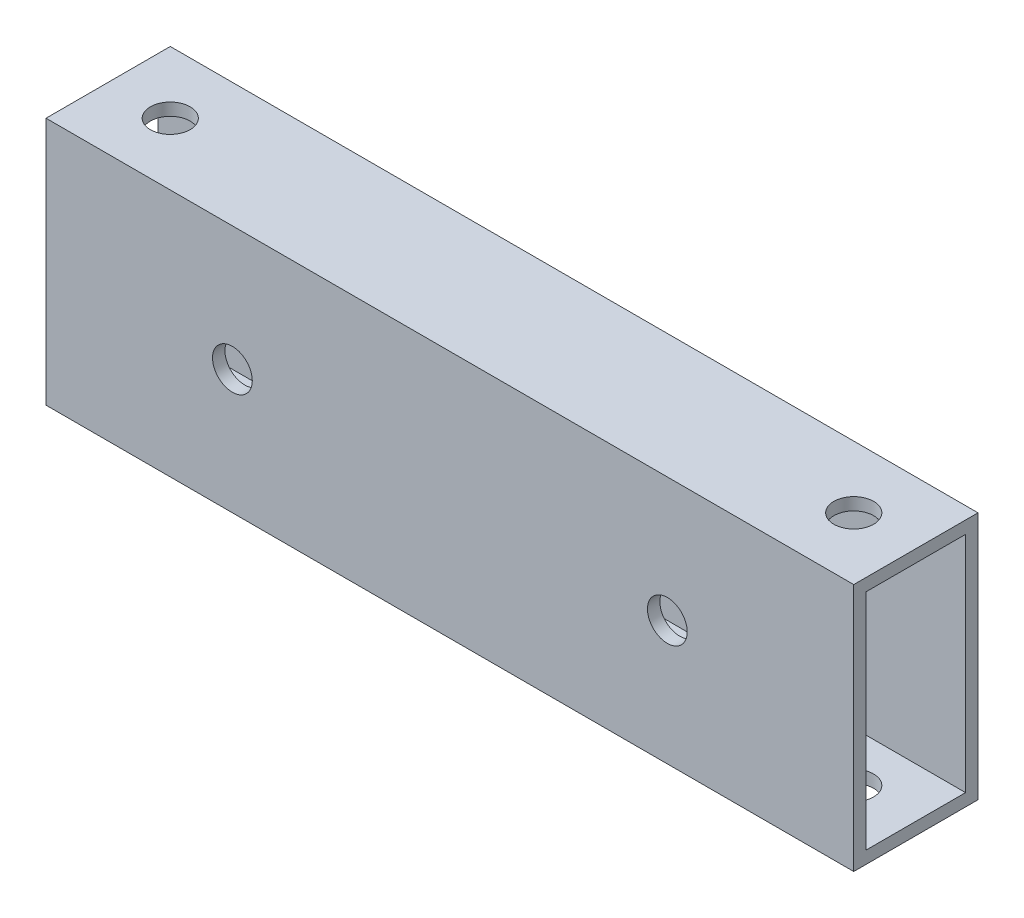
SolidWorks part; units mm, degrees
material "5052-H34"
ref_plane "正面" through (0, 0, 0) normal (0, 0, 1) x (1, 0, 0)
ref_plane "平面" through (0, 0, 0) normal (0, 1, 0) x (1, 0, 0)
ref_plane "右側面" through (0, 0, 0) normal (1, 0, 0) x (0, 0, -1)
sketch "ｽｹｯﾁ1" plane through (0, 0, 0) normal (1, 0, 0) x (0, 0, -1)
  line L1 (-5, 10) -> (5, 10)
  line L2 (-5, 10) -> (-5, -10)
  line L3 (-5, -10) -> (5, -10)
  line L4 (5, 10) -> (5, -10)
  line L5 (-5, 10) -> (5, -10) construction
  line L6 (-5, -10) -> (5, 10) construction
  point P0 (0, 0)
  dimension "D1" = 20
  dimension "D2" = 10
extrude "押し出し-薄板1" add sketch "ｽｹｯﾁ1" along normal blind 65 thin
sketch "ｽｹｯﾁ2" plane through (0, 0, 5) normal (0, 0, 1) x (1, 0, 0)
  line L0 (32.5, 10) -> (32.5, -10) construction
  line L1 (65, 10) -> (0, 10) construction
  line L2 (65, -10) -> (0, -10) construction
  line L3 (32.5, 0) -> (15, 0) construction
  circle A0 centre (15, 0) radius 1.6
  circle A1 centre (50, 0) radius 1.6
  dimension "D1" = 3.2
  dimension "D2" = 35
extrude "ｶｯﾄ - 押し出し1" cut sketch "ｽｹｯﾁ2" against normal through all
sketch "ｽｹｯﾁ3" plane through (0, 10, 0) normal (0, 1, 0) x (1, 0, 0)
  line L0 (32.5, 5) -> (32.5, -5) construction
  line L1 (65, 5) -> (0, 5) construction
  line L2 (65, -5) -> (0, -5) construction
  line L3 (32.5, 0) -> (5, 0) construction
  circle A0 centre (5, 0) radius 1.6
  circle A1 centre (60, 0) radius 1.6
  dimension "D1" = 3.2
  dimension "D2" = 55
extrude "ｶｯﾄ - 押し出し2" cut sketch "ｽｹｯﾁ3" against normal through all
